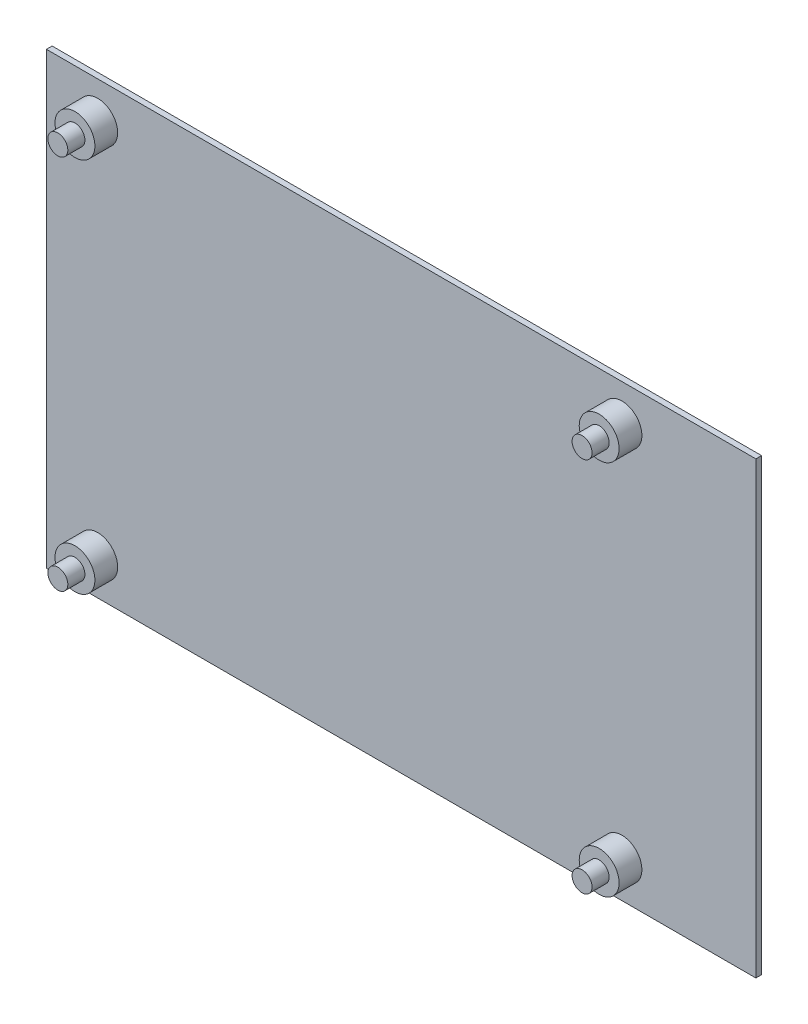
SolidWorks part; units mm, degrees
ref_plane "Front Plane" through (0, 0, 0) normal (0, 0, 1) x (1, 0, 0)
ref_plane "Top Plane" through (0, 0, 0) normal (0, 1, 0) x (1, 0, 0)
ref_plane "Right Plane" through (0, 0, 0) normal (1, 0, 0) x (0, 0, -1)
sketch "Sketch1" plane through (0, 0, 0) normal (0, 0, 1) x (1, 0, 0)
  line L0 (47.25, 32.5) -> (47.25, 34.2) construction
  line L1 (47.25, 34.2) -> (-77.25, 34.2)
  line L2 (47.25, 34.2) -> (47.25, -44.7)
  line L3 (47.25, -44.7) -> (-77.25, -44.7)
  line L4 (-77.25, 34.2) -> (-77.25, -44.7)
  line L5 (47.25, 34.2) -> (-77.25, -44.7) construction
  line L6 (47.25, -44.7) -> (-77.25, 34.2) construction
  line L7 (-77.25, -44.7) -> (50.25, -44.7) construction
  point P0 (-15, -5.25)
extrude "Boss-Extrude1" add sketch "Sketch1" along normal blind 1
sketch "Sketch2" plane through (0, 0, 1) normal (0, 0, 1) x (1, 0, 0)
  line L1 (23.75, 27.75) -> (-68.25, 27.75) construction
  line L2 (23.75, 27.75) -> (23.75, -38.25) construction
  line L3 (23.75, -38.25) -> (-68.25, -38.25) construction
  line L4 (-68.25, 27.75) -> (-68.25, -38.25) construction
  line L5 (23.75, 27.75) -> (-68.25, -38.25) construction
  line L6 (23.75, -38.25) -> (-68.25, 27.75) construction
  line L7 (-77.25, 34.2) -> (-77.25, -44.7) construction
  line L8 (-49.3515, -38.25) -> (-49.3515, -44.7) construction
  line L9 (-77.25, -44.7) -> (47.25, -44.7) construction
  line L10 (-49.3515, 27.75) -> (-49.3515, 34.2) construction
  line L11 (47.25, 34.2) -> (-77.25, 34.2) construction
  circle A0 centre (-68.25, 27.75) radius 3.5
  circle A1 centre (23.75, 27.75) radius 3.5
  circle A2 centre (23.75, -38.25) radius 3.5
  circle A3 centre (-68.25, -38.25) radius 3.5
  point P0 (-22.25, -5.25)
  dimension "D4" = 7
  dimension "D1" = 92
  dimension "D2" = 66
  dimension "D3" = 9
extrude "Boss-Extrude2" add sketch "Sketch2" along normal blind 4
sketch "Sketch3" plane through (0, 0, 5) normal (0, 0, 1) x (1, 0, 0)
  circle A0 centre (-68.25, 27.75) radius 1.75
  circle A1 centre (23.75, 27.75) radius 1.75
  circle A2 centre (23.75, -38.25) radius 1.75
  circle A3 centre (-68.25, -38.25) radius 1.75
  dimension "D1" = 3.5
extrude "Boss-Extrude3" add sketch "Sketch3" along normal blind 3
